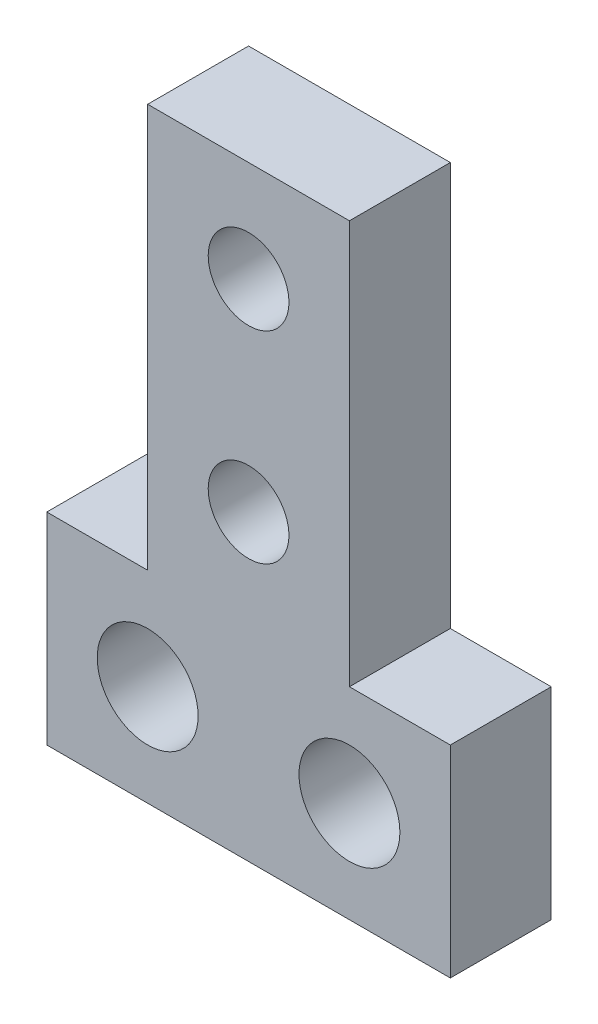
SolidWorks part; units mm, degrees
ref_plane "前视基准面" through (0, 0, 0) normal (0, 0, 1) x (1, 0, 0)
ref_plane "上视基准面" through (0, 0, 0) normal (0, 1, 0) x (1, 0, 0)
ref_plane "右视基准面" through (0, 0, 0) normal (1, 0, 0) x (0, 0, -1)
sketch "草图1" plane through (0, 0, 0) normal (0, 0, 1) x (1, 0, 0)
  line L1 (10, -5) -> (-10, -5)
  line L2 (10, -5) -> (10, 5)
  line L3 (10, 5) -> (-10, 5)
  line L4 (-10, -5) -> (-10, 5)
  line L5 (10, -5) -> (-10, 5) construction
  line L6 (10, 5) -> (-10, -5) construction
  circle A0 centre (-5, 0) radius 2.5
  circle A1 centre (5, 0) radius 2.5
  point P0 (0, 0)
  point P10 (0, 0)
  point P11 (0, 0)
  dimension "D3" = 5
  dimension "D4" = 5
  dimension "D1" = 10
  dimension "D2" = 20
  dimension "D5" = 10
  dimension "D6" = 5
extrude "凸台-拉伸1" add sketch "草图1" along normal blind 5
sketch "草图2" plane through (0, 0, 0) normal (0, 0, -1) x (-1, 0, 0)
  line L0 (-10, 5) -> (10, 5) construction
  line L1 (5, 5) -> (-5, 5)
  line L2 (5, 5) -> (5, 25)
  line L3 (5, 25) -> (-5, 25)
  line L4 (-5, 5) -> (-5, 25)
  line L5 (5, 5) -> (-5, 25) construction
  line L6 (5, 25) -> (-5, 5) construction
  circle A0 centre (0, 20) radius 2
  circle A1 centre (0, 10) radius 2
  point P4 (0, 15)
  dimension "D5" = 4
  dimension "D6" = 4
  dimension "D1" = 20
  dimension "D2" = 10
  dimension "D3" = 10
  dimension "D4" = 5
extrude "凸台-拉伸2" add sketch "草图2" against normal blind 5
